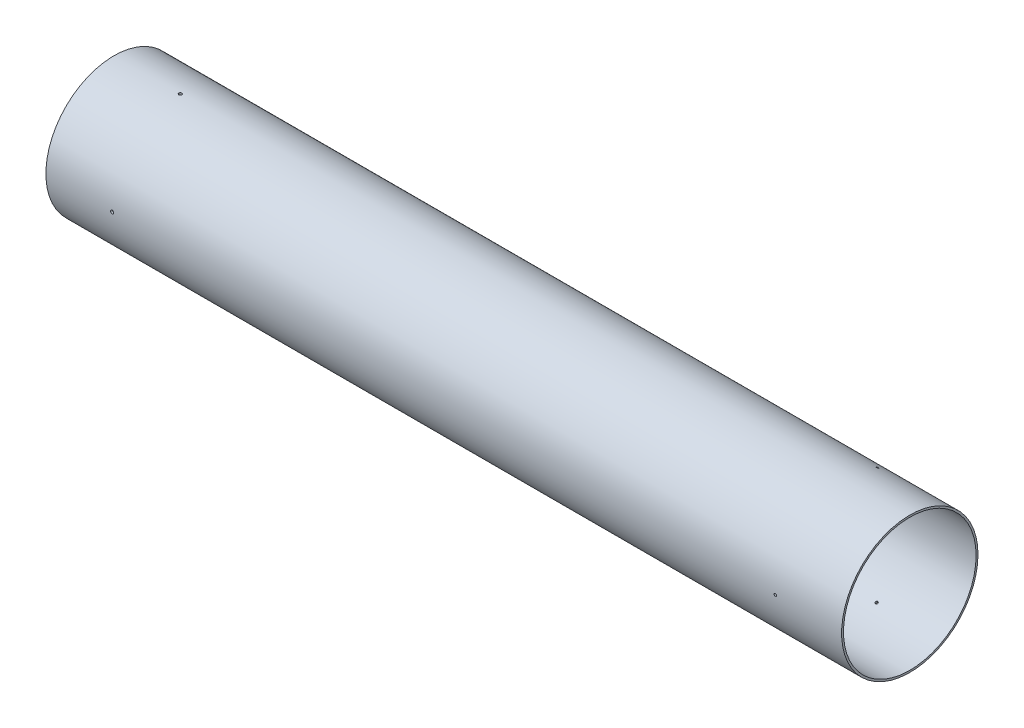
SolidWorks part; units mm, degrees
material "E-Glass Fiber"
ref_plane "Front Plane" through (0, 0, 0) normal (0, 0, 1) x (1, 0, 0)
ref_plane "Top Plane" through (0, 0, 0) normal (0, 1, 0) x (1, 0, 0)
ref_plane "Right Plane" through (0, 0, 0) normal (1, 0, 0) x (0, 0, -1)
sketch "Sketch3" plane through (0, 0, 0) normal (1, 0, 0) x (0, 0, -1)
  circle A0 centre (0, 0) radius 78.359
  circle A1 centre (0, 0) radius 76.2
  dimension "D1" = 156.718
  dimension "D2" = 152.4
extrude "Boss-Extrude1" add sketch "Sketch3" along normal blind 914.4
sketch "Sketch4" plane through (0, 0, 0) normal (0, 0, 1) x (1, 0, 0)
  line L0 (914.4, -78.359) -> (914.4, 78.359) construction
  circle A0 centre (838.2, 0) radius 1.4122
  dimension "D2" = 2.8245
  dimension "D1" = 76.2
extrude "Cut-Extrude1" cut sketch "Sketch4" along normal up to surface (78.359 mm away)
pattern_circular "CirPattern1" count 3 over 360 about axis through (914.4, 0, 0) along (1, 0, 0) of "Cut-Extrude1"
sketch "Sketch5" plane through (0, 0, 0) normal (0, 0, 1) x (1, 0, 0)
  circle A0 centre (76.2, 0) radius 1.7859
  point P2 (0, 0)
  dimension "D1" = 3.5719
  dimension "D2" = 76.2
extrude "Cut-Extrude2" cut sketch "Sketch5" along normal up to surface (78.359 mm away)
pattern_circular "CirPattern2" count 4 over 360 about axis through (0, 0, 0) along (1, 0, 0) of "Cut-Extrude2"
